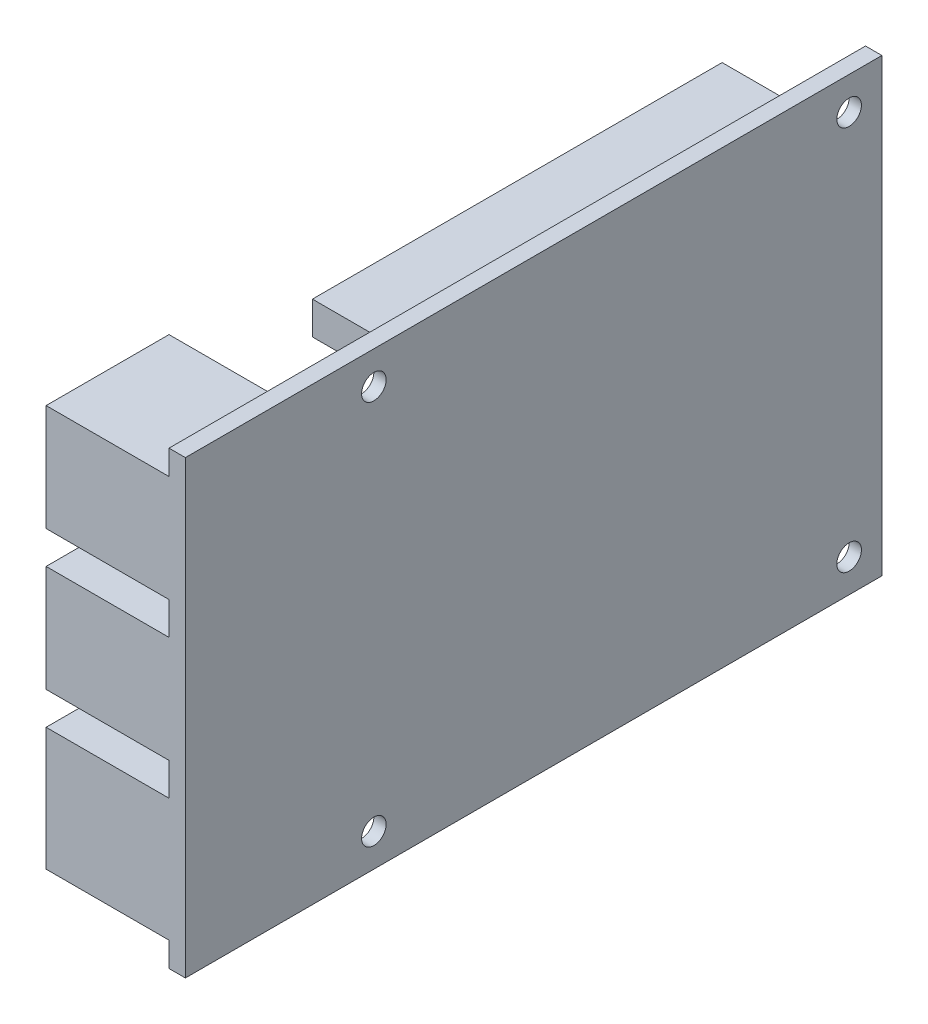
SolidWorks part; units mm, degrees
ref_plane "Plan de face" through (0, 0, 0) normal (0, 0, 1) x (1, 0, 0)
ref_plane "Plan de dessus" through (0, 0, 0) normal (0, 1, 0) x (1, 0, 0)
ref_plane "Plan de droite" through (0, 0, 0) normal (1, 0, 0) x (0, 0, -1)
sketch "Esquisse1" plane through (0, 0, 0) normal (1, 0, 0) x (0, 0, -1)
  line L1 (-42.5, -27.5) -> (42.5, -27.5)
  line L2 (-42.5, -27.5) -> (-42.5, 27.5)
  line L3 (-42.5, 27.5) -> (42.5, 27.5)
  line L4 (42.5, -27.5) -> (42.5, 27.5)
  line L5 (-42.5, -27.5) -> (42.5, 27.5) construction
  line L6 (-42.5, 27.5) -> (42.5, -27.5) construction
  point P0 (0, 0)
  dimension "D1" = 55
  dimension "D2" = 85
extrude "Boss.-Extru.1" add sketch "Esquisse1" along normal blind 2
sketch "Esquisse2" plane through (0, 0, 0) normal (-1, 0, 0) x (0, 0, 1)
  line L0 (42.5, 27.5) -> (42.5, -27.5) construction
  line L1 (42.5, -24.5) -> (22.5, -24.5)
  line L2 (42.5, -24.5) -> (42.5, -9.5)
  line L3 (42.5, -9.5) -> (22.5, -9.5)
  line L4 (22.5, -24.5) -> (22.5, -9.5)
  line L5 (-42.5, 27.5) -> (42.5, 27.5) construction
  line L6 (42.5, -5.5) -> (27.5, -5.5)
  line L7 (42.5, -5.5) -> (42.5, 7.5)
  line L8 (42.5, 7.5) -> (27.5, 7.5)
  line L9 (27.5, -5.5) -> (27.5, 7.5)
  line L10 (42.5, 11.5) -> (27.5, 11.5)
  line L11 (42.5, 11.5) -> (42.5, 24.5)
  line L12 (42.5, 24.5) -> (27.5, 24.5)
  line L13 (27.5, 11.5) -> (27.5, 24.5)
  dimension "D1" = 15
  dimension "D2" = 13
  dimension "D3" = 20
  dimension "D4" = 15
  dimension "D5" = 15
  dimension "D6" = 13
  dimension "D7" = 3
  dimension "D8" = 4
  dimension "D9" = 4
extrude "Boss.-Extru.2" add sketch "Esquisse2" along normal blind 15 contours L2 L1 L4 L3 | L7 L6 L9 L8 | L11 L10 L13 L12
sketch "Esquisse3" plane through (0, 0, 0) normal (-1, 0, 0) x (0, 0, 1)
  line L0 (-42.5, -27.5) -> (-42.5, 27.5) construction
  line L1 (-42.5, 27.5) -> (42.5, 27.5) construction
  line L3 (42.5, 27.5) -> (42.5, 24.5) construction
  line L4 (-48.6726, 0) -> (45.7389, 0) construction
  circle A0 centre (-38.5, 23.5) radius 1.5
  circle A1 centre (19.5, 23.5) radius 1.5
  circle A2 centre (-38.5, -23.5) radius 1.5
  circle A3 centre (19.5, -23.5) radius 1.5
  dimension "D1" = 3
  dimension "D2" = 3
  dimension "D3" = 4
  dimension "D4" = 4
  dimension "D5" = 4
  dimension "D6" = 23
extrude "Enlèv. mat.-Extru.1" cut sketch "Esquisse3" against normal blind 15
sketch "Esquisse5" plane through (0, 0, 0) normal (-1, 0, 0) x (0, 0, 1)
  line L0 (-48.2559, 0) -> (62.0809, 0) construction
  circle A0 centre (19.5, 23.5) radius 2.5
  circle A1 centre (-38.5, 23.5) radius 2.5
  circle A2 centre (-38.5, -23.5) radius 2.5
  circle A3 centre (19.5, -23.5) radius 2.5
  dimension "D1" = 5
  dimension "D2" = 5
extrude "Enlèv. mat.-Extru.2" cut sketch "Esquisse5" against normal blind 0.5
sketch "Esquisse6" plane through (0, 0, 0) normal (-1, 0, 0) x (0, 0, 1)
  line L0 (-42.5, 27.5) -> (42.5, 27.5) construction
  line L1 (16, 21.5) -> (-34, 21.5)
  line L2 (16, 21.5) -> (16, 25.5)
  line L3 (16, 25.5) -> (-34, 25.5)
  line L4 (-34, 21.5) -> (-34, 25.5)
  circle A0 centre (19.5, 23.5) radius 2.5 construction
  point P4 (-34, 23.5)
  dimension "D2" = 3.5
  dimension "D1" = 50
  dimension "D3" = 4
  dimension "D4" = 2
extrude "Boss.-Extru.3" add sketch "Esquisse6" along normal blind 9
